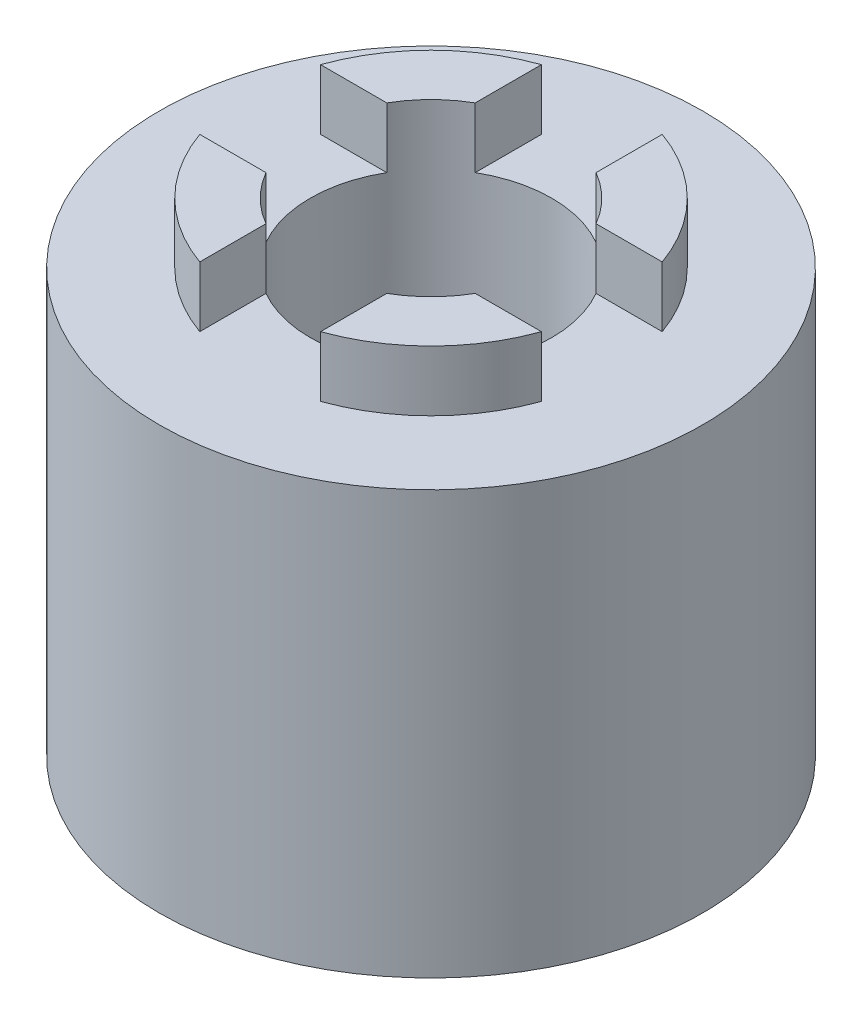
SolidWorks part; units mm, degrees
ref_plane "Front Plane" through (0, 0, 0) normal (0, 0, 1) x (1, 0, 0)
ref_plane "Top Plane" through (0, 0, 0) normal (0, 1, 0) x (1, 0, 0)
ref_plane "Right Plane" through (0, 0, 0) normal (1, 0, 0) x (0, 0, -1)
sketch "Sketch2" plane through (0, 0, 0) normal (0, 1, 0) x (1, 0, 0)
  circle A0 centre (0, 0) radius 28.575
  circle A1 centre (0, 0) radius 12.7
  dimension "D1" = 57.15
  dimension "D2" = 25.4
extrude "Boss-Extrude2" add sketch "Sketch2" along normal blind 50.8 contours A0 | A1
sketch "Sketch4" plane through (0, 50.8, 0) normal (0, 1, 0) x (1, 0, 0)
  line L1 (38.1, 6.35) -> (-38.1, 6.35)
  line L2 (38.1, 6.35) -> (38.1, -6.35)
  line L3 (38.1, -6.35) -> (-38.1, -6.35)
  line L4 (-38.1, 6.35) -> (-38.1, -6.35)
  line L5 (0, -6.35) -> (0, 6.35) construction
  line L6 (38.1, 0) -> (-38.1, 0) construction
  point P0 (0, 0)
  dimension "D1" = 12.7
extrude "Cut-Extrude7" cut sketch "Sketch4" against normal blind 6.35
sketch "Sketch8" plane through (0, 0, 0) normal (0, -1, 0) x (1, 0, 0)
  line L0 (-18.9871, -3.532) -> (16.8152, 9.499)
  line L1 (-18.9871, -3.532) -> (-16.8152, -9.499)
  line L2 (16.8152, 9.499) -> (18.9871, 3.532)
  line L3 (-16.8152, -9.499) -> (18.9871, 3.532)
  line L4 (-18.9871, -3.532) -> (18.9871, 3.532) construction
  line L5 (16.8152, 9.499) -> (-16.8152, -9.499) construction
  point P1 (0, 0)
pattern_circular "CirPattern1" count 2 every 90 about axis through (0, 50.8, 0) along (0, 1, 0) of "Cut-Extrude7"
sketch "Sketch9" plane through (0, 0, 0) normal (0, -1, 0) x (1, 0, 0)
  circle A0 centre (0, 0) radius 22.225
  circle A1 centre (0, 0) radius 28.575 construction
  dimension "D1" = 6.35
extrude "Cut-Extrude8" cut sketch "Sketch9" against normal blind 25.4
sketch "Sketch10" plane through (0, 50.8, 0) normal (0, 1, 0) x (1, 0, 0)
  circle A0 centre (0, 0) radius 28.575
  circle A1 centre (0, 0) radius 19.05
  dimension "D1" = 57.15
  dimension "D2" = 38.1
extrude "Cut-Extrude10" cut sketch "Sketch10" against normal blind 6.35
